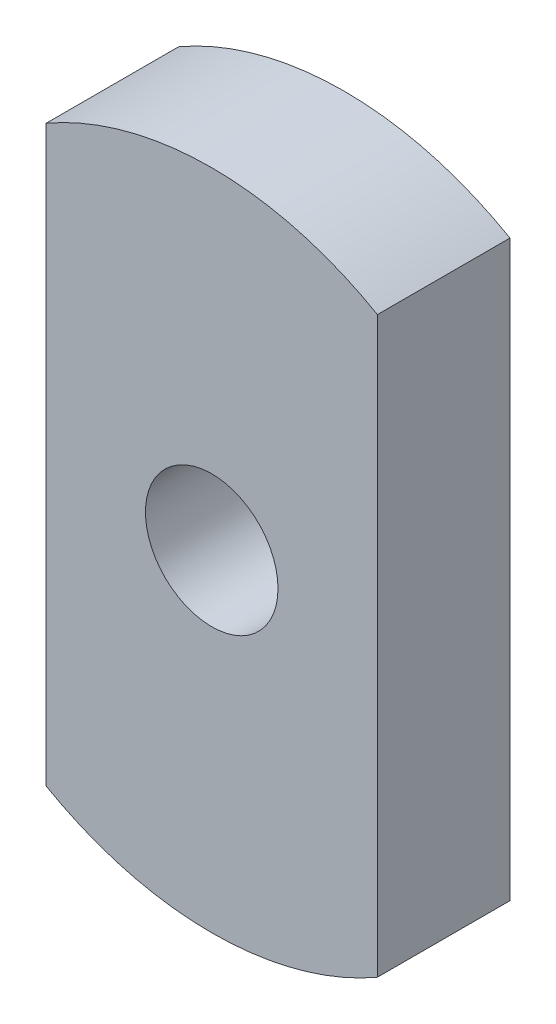
SolidWorks part; units mm, degrees
ref_plane "Front Plane" through (0, 0, 0) normal (0, 0, 1) x (1, 0, 0)
ref_plane "Top Plane" through (0, 0, 0) normal (0, 1, 0) x (1, 0, 0)
ref_plane "Right Plane" through (0, 0, 0) normal (1, 0, 0) x (0, 0, -1)
sketch "Sketch1" plane through (0, 0, 0) normal (0, 0, 1) x (1, 0, 0)
  line L0 (-5, 8.6603) -> (-5, -8.6603)
  line L1 (5, 8.6603) -> (5, -8.6603)
  circle A0 centre (0, 0) radius 10 construction
  circle A1 centre (0, 0) radius 2
  arc A2 (-5, 8.6603) -> (5, 8.6603) centre (0, 0) cw
  arc A3 (-5, -8.6603) -> (5, -8.6603) centre (0, 0) ccw
  dimension "D1" = 20
  dimension "D2" = 4
  dimension "D3" = 5
extrude "Boss-Extrude1" add sketch "Sketch1" along normal blind 4
